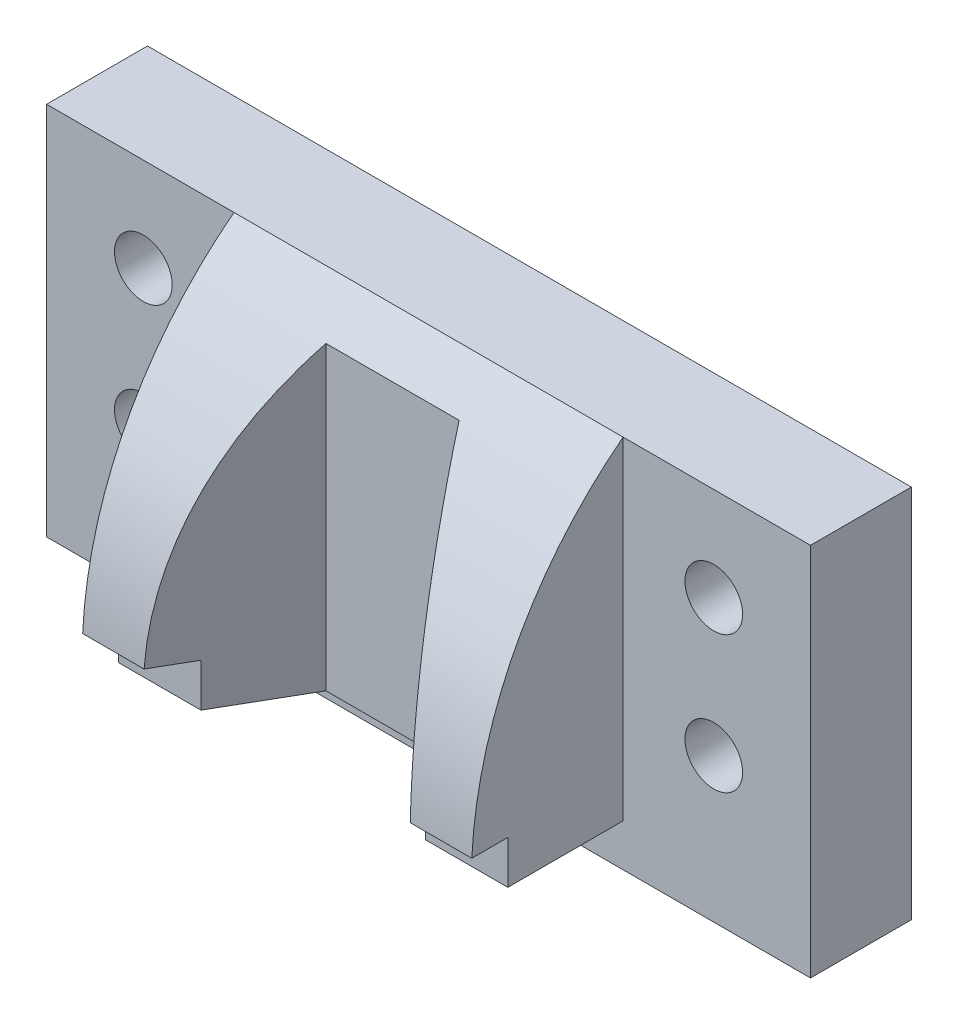
SolidWorks part; units mm, degrees
ref_plane "Front Plane" through (0, 0, 0) normal (0, 0, 1) x (1, 0, 0)
ref_plane "Top Plane" through (0, 0, 0) normal (0, 1, 0) x (1, 0, 0)
ref_plane "Right Plane" through (0, 0, 0) normal (1, 0, 0) x (0, 0, -1)
sketch "Sketch1" plane through (0, 0, 0) normal (0, 0, 1) x (1, 0, 0)
  line L1 (-53, 26) -> (53, 26)
  line L2 (-53, 26) -> (-53, -26)
  line L3 (-53, -26) -> (53, -26)
  line L4 (53, 26) -> (53, -26)
  line L5 (-53, 26) -> (53, -26) construction
  line L6 (-53, -26) -> (53, 26) construction
  point P0 (0, 0)
  dimension "D1" = 106
  dimension "D2" = 52
extrude "Boss-Extrude1" add sketch "Sketch1" along normal blind 14
sketch "Sketch2" plane through (0, 0, 14) normal (0, 0, 1) x (1, 0, 0)
  line L0 (53, 26) -> (-53, 26) construction
  circle A0 centre (39.5764, 13) radius 4
  circle A1 centre (39.5764, -6) radius 4
  dimension "D1" = 8
  dimension "D2" = 13
  dimension "D3" = 32
extrude "Cut-Extrude1" cut sketch "Sketch2" against normal blind 14
ref_plane "Plane1" through (0, 0, 0) normal (-1, 0, 0) x (0, 0, 1)
mirror "Mirror1" about plane through (0, 0, 0) normal (-1, 0, 0) of "Cut-Extrude1"
ref_plane "Plane2" through (0, 0, 0) normal (-1, 0, 0) x (0, 0, 1)
sketch "Sketch4" plane through (0, 0, 0) normal (-1, 0, 0) x (0, 0, 1)
  line L0 (14, 26) -> (14, -20.1089)
  line L1 (14, 26) -> (0, 26) construction
  line L2 (14, 26) -> (14, -26) construction
  line L3 (14, -20.1089) -> (30, -20.1089)
  line L4 (30, -20.1089) -> (30, -14.1089)
  line L5 (30, -14.1089) -> (35, -14.1089)
  arc A0 (14, 26) -> (35, -14.1089) centre (-18.9332, -16.7949) cw
  dimension "D1" = 5
extrude "Boss-Extrude2" add sketch "Sketch4" along normal mid plane 54
sketch "Sketch6" plane through (0, -20.1089, 0) normal (0, -1, 0) x (1, 0, 0)
  line L0 (-27, 35) -> (27, 35) construction
  line L1 (-9.2376, 19) -> (-18.4752, 35)
  line L2 (-9.2376, 19) -> (9.2376, 19)
  line L3 (-9.2376, 19) -> (-9.2376, 49.4496) construction
  line L4 (0, 0) -> (0, 55.2992) construction
  line L5 (9.2376, 19) -> (18.4752, 35)
  line L6 (-18.4752, 35) -> (18.4752, 35)
  circle A0 centre (0, 35) radius 16 construction
  dimension "D1" = 32
  dimension "D2" = 30
extrude "Cut-Extrude2" cut sketch "Sketch6" against normal through all
